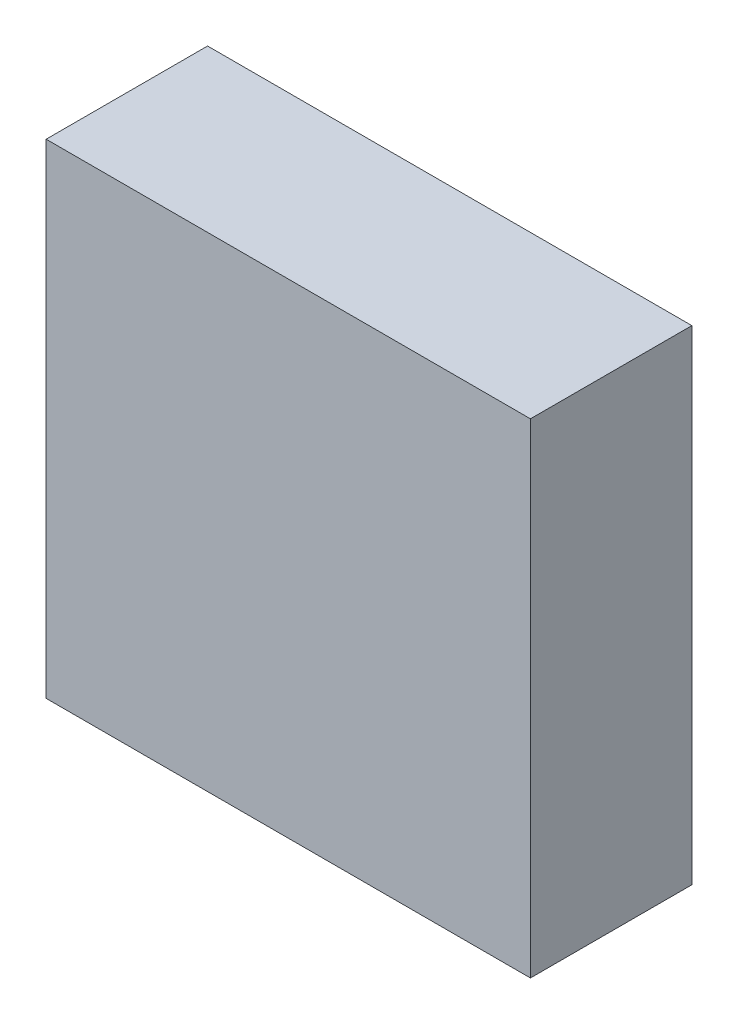
SolidWorks part; units mm, degrees
ref_plane "前视基准面" through (0, 0, 0) normal (0, 0, 1) x (1, 0, 0)
ref_plane "上视基准面" through (0, 0, 0) normal (0, 1, 0) x (1, 0, 0)
ref_plane "右视基准面" through (0, 0, 0) normal (1, 0, 0) x (0, 0, -1)
other "Configuration Table"
sketch "草图1" plane through (0, 0, 0) normal (0, 0, 1) x (1, 0, 0)
  line L1 (0, 0) -> (60, 0)
  line L2 (0, 0) -> (0, 60)
  line L3 (0, 60) -> (60, 60)
  line L4 (60, 0) -> (60, 60)
extrude "Sample_workpiece_60x60x20" add sketch "草图1" along normal blind 20
